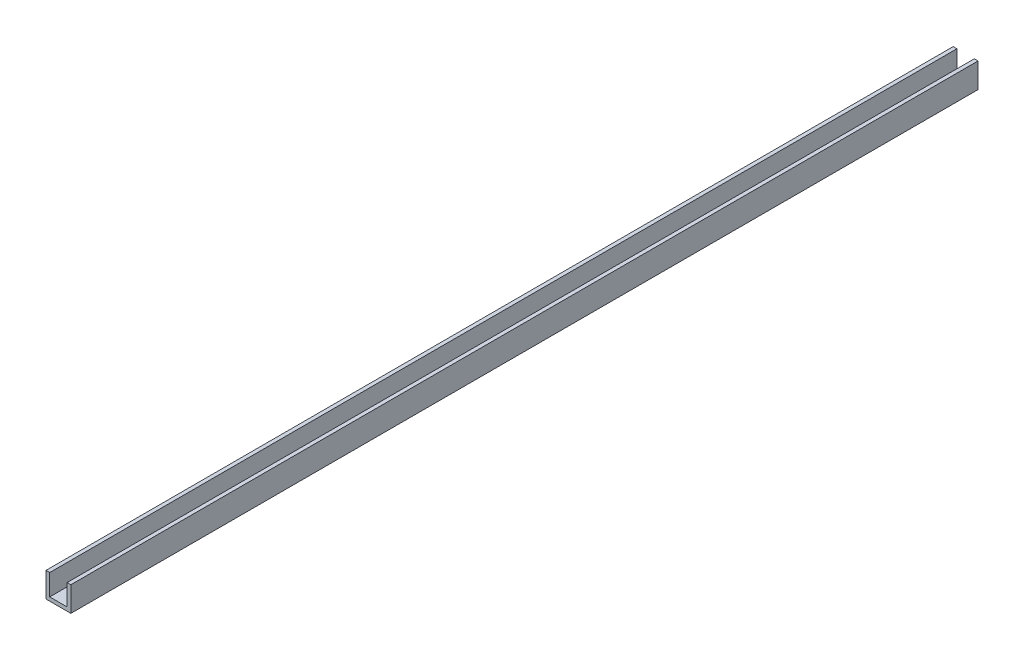
SolidWorks part; units mm, degrees
material "1060 Сплав"
ref_plane "Спереди" through (0, 0, 0) normal (0, 0, 1) x (1, 0, 0)
ref_plane "Сверху" through (0, 0, 0) normal (0, 1, 0) x (1, 0, 0)
ref_plane "Справа" through (0, 0, 0) normal (1, 0, 0) x (0, 0, -1)
sketch "Эскиз1" plane through (0, 0, 0) normal (0, 0, 1) x (1, 0, 0)
  line L0 (0, 0) -> (10, 0)
  line L1 (10, 0) -> (10, 10)
  line L2 (10, 10) -> (8.5, 10)
  line L3 (8.5, 10) -> (8.5, 1.5)
  line L4 (8.5, 1.5) -> (1.5, 1.5)
  line L5 (1.5, 1.5) -> (1.5, 10)
  line L6 (1.5, 10) -> (0, 10)
  line L7 (0, 10) -> (0, 0)
  dimension "D1" = 1.5
  dimension "D2" = 1.5
  dimension "D3" = 10
extrude "Бобышка-Вытянуть1" add sketch "Эскиз1" along normal blind 365
sketch "Эскиз2" plane through (10, 0, 0) normal (1, 0, 0) x (0, 0, -1)
  line L0 (-365, 5) -> (0, 5) construction
  line L1 (-365, 0) -> (-365, 10) construction
  line L2 (0, 0) -> (0, 10) construction
equation "\"ATX.Case.01.Dimension.1\"=499"
equation "\"ATX.Case.01.Dimension.2\"=375"
equation "\"ATX.Case.01.Profile.20.Width\"=20"
equation "\"ATX.Case.01.Profile.20.Thickness\" = 1.5"
equation "\"ATX.Case.01.Profile.10.Width\"=10"
equation "\"ATX.Case.01.Profile.10.Thickness\"=1.5"
equation "\"D2@Эскиз1\"= \"ATX.Case.01.Profile.10.Thickness\""
equation "\"D1@Эскиз1\"= \"ATX.Case.01.Profile.10.Thickness\""
equation "\"D3@Эскиз1\"= \"ATX.Case.01.Profile.10.Width\""
equation "\"D1@Бобышка-Вытянуть1\"=\"ATX.Case.01.Dimension.1\" - \"ATX.Case.01.Profile.20.Thickness\" * 2мм * 2"
